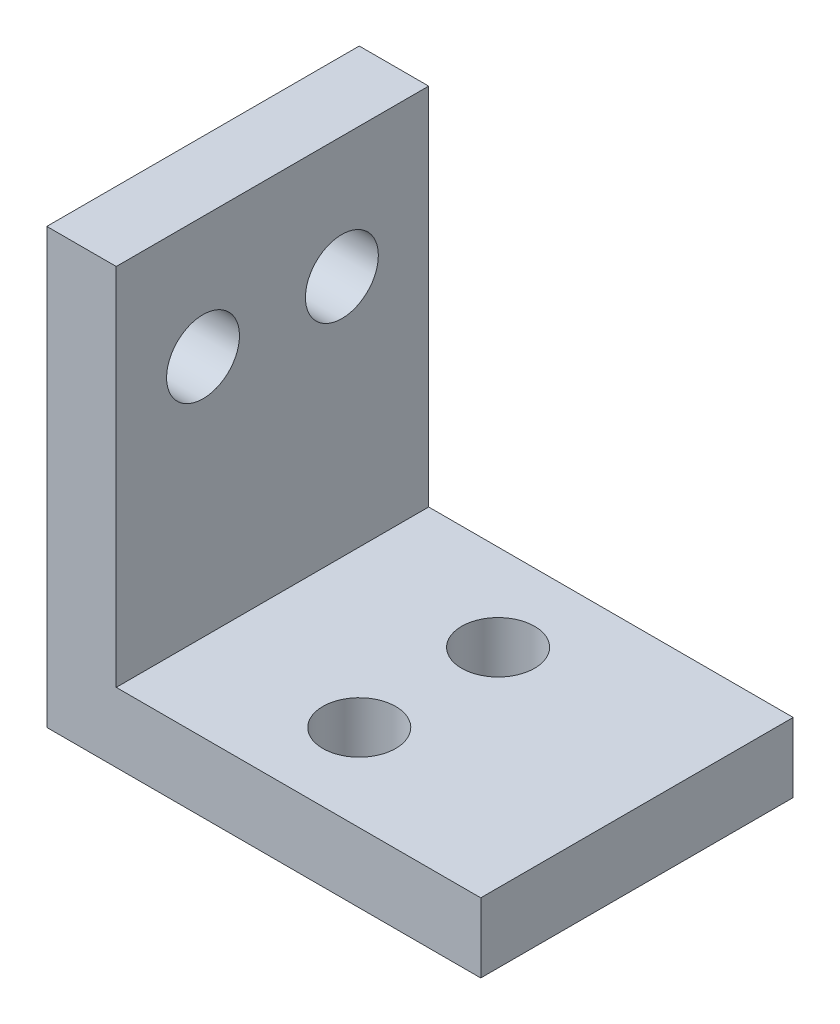
SolidWorks part; units mm, degrees
material "AISI 1015 钢，冷拔 (SS)"
ref_plane "前视基准面" through (0, 0, 0) normal (0, 0, 1) x (1, 0, 0)
ref_plane "上视基准面" through (0, 0, 0) normal (0, 1, 0) x (1, 0, 0)
ref_plane "右视基准面" through (0, 0, 0) normal (1, 0, 0) x (0, 0, -1)
other "Configuration Table"
sketch "草图1" plane through (0, 0, 0) normal (0, 0, 1) x (1, 0, 0)
  line L0 (0, 25) -> (0, 0)
  line L1 (0, 0) -> (25, 0)
  line L2 (25, 0) -> (25, 4)
  line L3 (25, 4) -> (4, 4)
  line L4 (4, 4) -> (4, 25)
  line L5 (4, 25) -> (0, 25)
  dimension "D1" = 4
  dimension "D2" = 4
  dimension "D3" = 25
  dimension "D4" = 25
extrude "凸台-拉伸1" add sketch "草图1" along normal blind 18
sketch "草图4" plane through (0, 4, 0) normal (0, 1, 0) x (1, 0, 0)
  line L0 (25, 0) -> (4, 0) construction
  line L2 (4, -18) -> (4, 0) construction
  line L3 (25, -18) -> (4, -18) construction
  line L5 (4, -18) -> (4, 0) construction
  circle A0 centre (13, -5) radius 2.1
  circle A1 centre (13, -13) radius 2.1
  dimension "D2" = 4.2
  dimension "D1" = 9
  dimension "D3" = 5
  dimension "D4" = 5
  dimension "D5" = 9
extrude "切除-拉伸3" cut sketch "草图4" against normal blind 38
sketch "草图5" plane through (0, 0, 0) normal (-1, 0, 0) x (0, 0, 1)
  line L1 (0, 25) -> (0, 0) construction
  line L2 (18, 0) -> (0, 0) construction
  line L3 (18, 25) -> (18, 0) construction
  circle A0 centre (5, 18) radius 2.1
  circle A1 centre (13, 18) radius 2.1
  dimension "D1" = 4.2
  dimension "D2" = 18
  dimension "D3" = 5
  dimension "D4" = 5
  dimension "D5" = 18
extrude "切除-拉伸4" cut sketch "草图5" against normal blind 38
